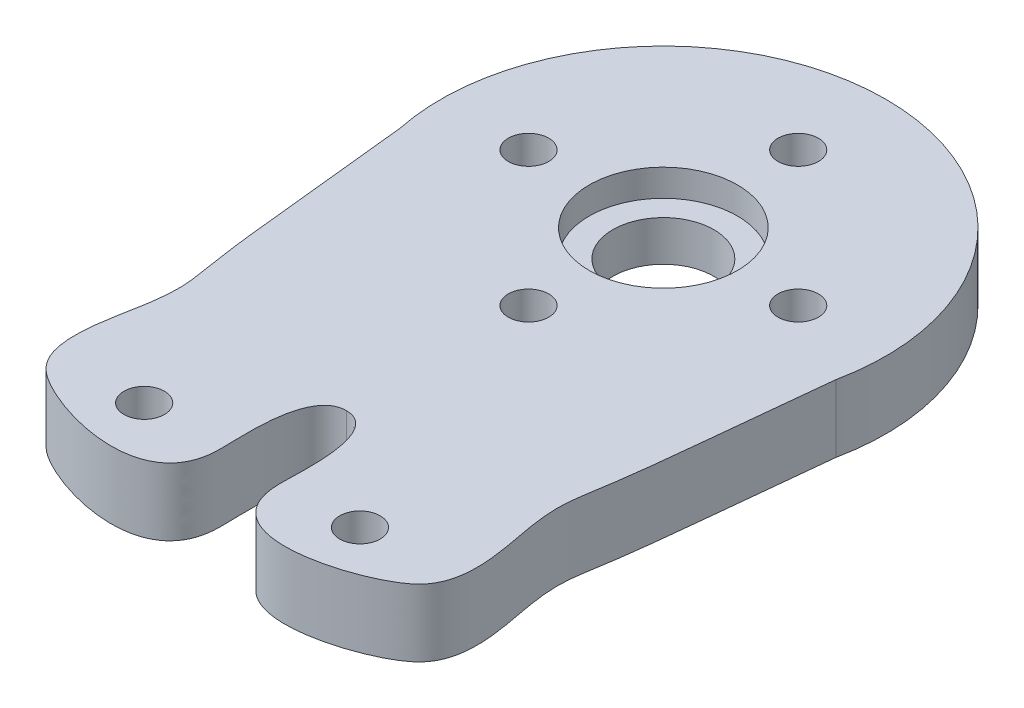
SolidWorks part; units mm, degrees
material "Acrílico (Impacto medio-alto)"
ref_plane "Alzado" through (0, 0, 0) normal (0, 0, 1) x (1, 0, 0)
ref_plane "Planta" through (0, 0, 0) normal (0, 1, 0) x (1, 0, 0)
ref_plane "Vista lateral" through (0, 0, 0) normal (1, 0, 0) x (0, 0, -1)
sketch "Croquis1" plane through (0, 0, 0) normal (0, 1, 0) x (1, 0, 0)
  line L0 (0, 0) -> (16.5, 0) construction
  circle A0 centre (0, 0) radius 16.5
  circle A1 centre (0, 0) radius 3.75
  circle A2 centre (10, 0) radius 1.5
  circle A3 centre (0, -10) radius 1.5
  circle A4 centre (-10, 0) radius 1.5
  circle A5 centre (0, 10) radius 1.5
  point P16 (0, 0)
  dimension "D1" = 33
  dimension "D2" = 7.5
  dimension "D3" = 3
  dimension "D4" = 6.5
  dimension "D5" = 4
extrude "Saliente-Extruir1" add sketch "Croquis1" along normal blind 5
sketch "Croquis2" plane through (0, 5, 0) normal (0, 1, 0) x (1, 0, 0)
  circle A0 centre (0, 0) radius 5.5
  dimension "D1" = 11
extrude "Cortar-Extruir1" cut sketch "Croquis2" against normal blind 2
sketch "Croquis4" plane through (0, 5, 0) normal (0, 1, 0) x (1, 0, 0)
  circle A0 centre (10, 0) radius 3
  circle A2 centre (-10, 0) radius 3
  circle A3 centre (0, 10) radius 3
  circle A4 centre (0, -10) radius 3 [skipped]
  point P12 (0, 0)
  dimension "D1" = 6
  dimension "D2" = 4
extrude "Cortar-Extruir2" cut sketch "Croquis4" along normal blind 2.5 from surface at -5 starting at face at (0, 0, 16.5)
ref_plane "Plano1" through (0, 1, 0) normal (0, 1, 0) x (1, 0, 0)
sketch "Croquis8" plane through (0, 1, 0) normal (0, 1, 0) x (1, 0, 0)
  line L0 (31.0581, 33.6969) -> (874.9973, -25.3171) construction
sketch "Croquis6" plane through (0, 5, 0) normal (0, 1, 0) x (1, 0, 0)
  line L0 (0, 16.5) -> (0, -34.5) construction
  line L1 (0, -34.5) -> (-21.2426, -34.5) construction
  line L2 (301.9012, 624.3122) -> (1994.5679, 624.3122) construction
  line L3 (-16.5, -0.005) -> (0, -15.1621)
  line L4 (0, -15.1621) -> (16.5, -0.005)
  circle A0 centre (0, 0) radius 16.5 construction
  circle A1 centre (-8, -30.5) radius 1.5
  circle A2 centre (8, -30.5) radius 1.5
  spline S0 degree 3 poles (-16.5, -0.005) (-14.7897, -16.6019) (-14.7798, -16.439) (-14.2007, -20.5517) (-13.6355, -22.4856) (-15.7333, -30.4196) (-11.3764, -34.0736) (-1.5642, -36.498) (-2.4163, -27.9759) (-1.8888, -23.5) (0, -23.5) knots 0 0 0 0 0.196162 0.243215 0.470534 0.661031 0.708414 0.918147 0.949928 1 1 1 1
  spline S1 degree 3 poles (16.5, -0.005) (14.7897, -16.6019) (14.7798, -16.439) (14.2007, -20.5517) (13.6355, -22.4856) (15.7333, -30.4196) (11.3764, -34.0736) (1.5642, -36.498) (2.4163, -27.9759) (1.8888, -23.5) (0, -23.5) knots 0 0 0 0 0.196162 0.243215 0.470534 0.661031 0.708414 0.918147 0.949928 1 1 1 1
  dimension "D4" = 3
  dimension "D6" = 4
  dimension "D1" = 51
  dimension "D2" = 4.5
  dimension "D3" = 11
  dimension "D5" = 8
extrude "Saliente-Extruir3" add sketch "Croquis6" against normal blind 5
